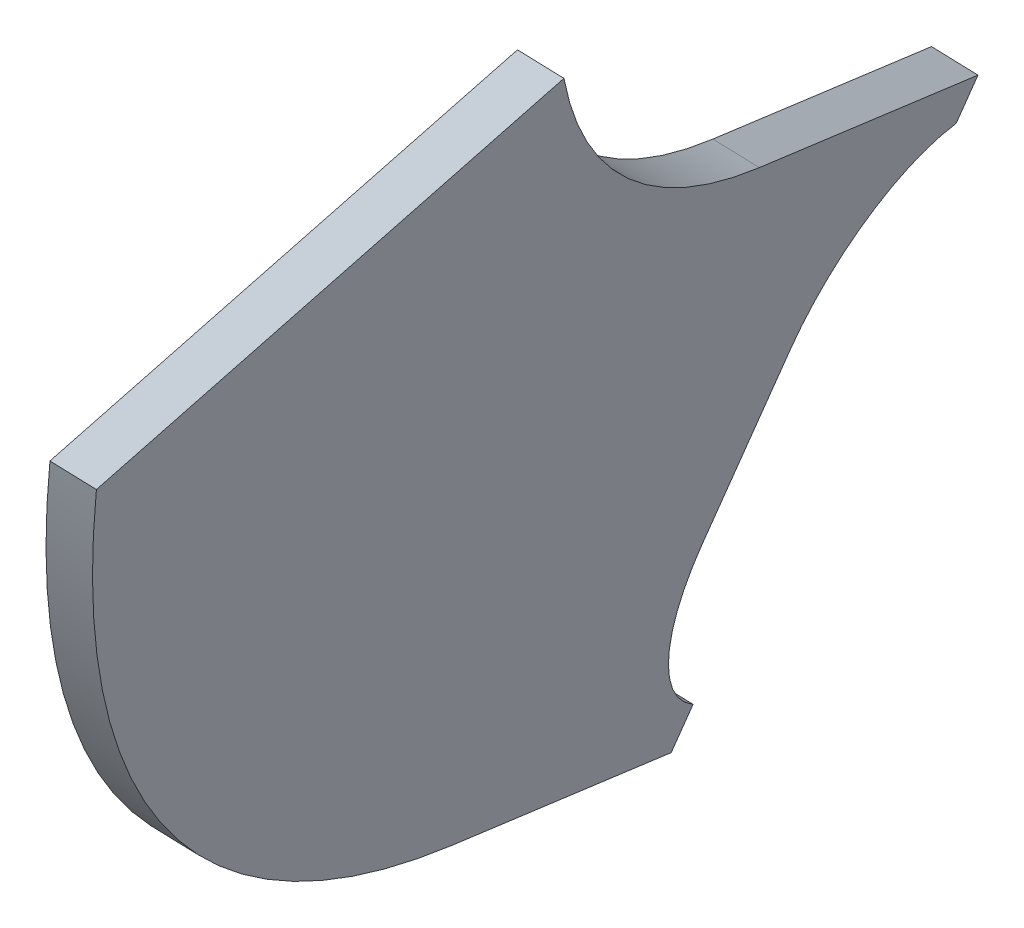
SolidWorks part; units mm, degrees
ref_plane "Front Plane" through (0, 0, 0) normal (0, 0, 1) x (1, 0, 0)
ref_plane "Top Plane" through (0, 0, 0) normal (0, 1, 0) x (1, 0, 0)
ref_plane "Right Plane" through (0, 0, 0) normal (1, 0, 0) x (0, 0, -1)
sketch "Sketch2" plane through (0, 0, 0) normal (0, 1, 0) x (1, 0, 0)
  line L0 (151.3, 0) -> (-151.3, 0) construction
  dimension "D1" = 302.6
ref_plane "Plane1" through (0, 0, 0) normal (0, 0.4067, 0.9135) x (-1, 0, 0)
sketch "Sketch3" plane through (0, 0, 0) normal (0, 0.4067, 0.9135) x (-1, 0, 0)
  line L0 (-136.8, 32.05) -> (-134.1, 32.05) construction
  line L1 (151.3, 176.2) -> (-151.3, 176.2) construction
  line L2 (151.3, 176.2) -> (151.3, 0) construction
  line L3 (151.3, 0) -> (-151.3, 0) construction
  line L4 (-151.3, 176.2) -> (-151.3, 0) construction
  line L5 (-151.3, 0) -> (151.3, 0) construction
  line L6 (-137.2598, 44.7696) -> (-140.8783, 19.0226) construction
  line L7 (-147.6, 46.65) -> (-134.1, 46.65) construction
  line L8 (-147.6, 46.65) -> (-147.6, 17.45) construction
  line L9 (-147.6, 17.45) -> (-134.1, 17.45) construction
  line L10 (-134.1, 46.65) -> (-134.1, 17.45) construction
  line L11 (-137.2598, 44.7696) -> (-142.6073, 45.5211) construction
  line L12 (-140.8783, 19.0226) -> (-146.2258, 19.7741) construction
  line L13 (-142.6073, 45.5211) -> (-146.2258, 19.7741) construction
  line L14 (-140.8783, 19.0226) -> (-133.9165, 18.0442) construction
  line L15 (-133.9165, 18.0442) -> (-134, 17.45) construction
  line L16 (-142.4371, 45.2952) -> (-137.4857, 44.5993)
  line L17 (-142.4371, 45.2952) -> (-145.9999, 19.9443)
  line L18 (-137.4857, 44.5993) -> (-141.0486, 19.2485)
  line L19 (-145.9999, 19.9443) -> (-141.0486, 19.2485)
  point P12 (-136.8, 32.05)
  dimension "D1" = 176.2
  dimension "D2" = 302.6
  dimension "D3" = 144.15
  dimension "D4" = 14.5
  dimension "D5" = 29.2
  dimension "D6" = 3.7
  dimension "D7" = 17.2
  dimension "D8" = 26
  dimension "D9" = 8
  dimension "D10" = 5.4
  dimension "D11" = 0.6
  dimension "D12" = 0.1
  dimension "D13" = 1.3742
  dimension "D14" = 5
  dimension "D15" = 0.2
  dimension "D16" = 0.2
  dimension "D17" = 0.2
extrude "Boss-Extrude1" add sketch "Sketch3" against normal blind 5
sketch "Sketch4" plane through (-3.4836, -22.6444, 10.0819) normal (-0.1392, -0.9047, 0.4028) x (0.9903, -0.1271, 0.0566)
  line L0 (152.7707, 16.0361) -> (147.2579, -3.1891) construction
  line L1 (142.3548, -5) -> (147.3548, 0) construction
  line L2 (152.7707, 16.0361) -> (151.2326, 16.4772) construction
  line L3 (151.2326, 16.4772) -> (146.3628, -0.506) construction
  line L4 (147.3548, -5) -> (147.3548, 0) construction
  line L5 (147.3548, -2.8514) -> (147.3548, -5)
  line L6 (147.3548, -5) -> (144.8548, -5)
  line L7 (142.3548, -5) -> (147.3548, -5) construction
  line L8 (147.2579, -3.1891) -> (147.3548, -2.8514)
  line L12 (142.3548, -2.5) -> (142.3548, -5)
  line L13 (142.3548, -5) -> (144.8548, -5)
  line L14 (142.3548, 0) -> (142.3548, -2.5)
  line L15 (142.3548, 0) -> (144.8548, 0)
  line L16 (144.8548, 0) -> (146.5079, 0)
  line L17 (146.5079, 0) -> (146.3628, -0.506)
  line L18 (142.3548, 0) -> (147.3548, 0) construction
  arc A0 (147.2579, -3.1891) -> (146.3628, -0.506) centre (144.8548, -2.5) cw construction
  arc A1 (144.8548, -5) -> (147.2579, -3.1891) centre (144.8548, -2.5) ccw
  arc A3 (142.3548, -2.5) -> (144.8548, -5) centre (144.8548, -2.5) ccw
  arc A4 (142.3548, -2.5) -> (144.8548, 0) centre (144.8548, -2.5) cw
  arc A5 (144.8548, 0) -> (146.3628, -0.506) centre (144.8548, -2.5) cw
  dimension "D2" = 2.5
  dimension "D1" = 1.6
  dimension "D3" = 16
  dimension "D4" = 20
extrude "Cut-Extrude1" cut sketch "Sketch4" against normal through all contours A1 L6 L8 | A3 L5 L6 | L5 A4 L8 | L8 A5 L17
ref_plane "Plane2" through (135.5824, -33.3758, -28.1152) normal (0.9519, -0.2343, -0.1974) x (-0.191, 0.0501, -0.9803)
sketch3d "3DSketch1"
  line L0 (149.6285, 0, 0) -> (156.8218, 0, 34.6885) construction
  line L1 (156.8218, 0, 34.6885) -> (151.3, -80.4834, 35.8335) construction
  line L2 (151.3, -160.9667, 71.667) -> (151.3, 0, 0) construction
  line L3 (151.3, 0, 0) -> (-151.3, 0, 0) construction
  line L4 (145.904, -19.5049, 5.1932) -> (150.827, -13.0853, 21.3129)
  line L5 (145.904, -19.5049, 5.1932) -> (142.3412, -42.664, 15.5044)
  line L6 (142.3412, -42.664, 15.5044) -> (147.2641, -36.2444, 31.624)
  line L7 (156.8218, 0, 34.6885) -> (162.2766, 0, 60.9937)
  line L8 (156.8218, 0, 34.6885) -> (160.157, 10.0034, 38.8972) construction
  line L9 (162.2766, 0, 60.9937) -> (160.157, 10.0034, 38.8972) construction
  line L10 (142.3412, -42.664, 15.5044) -> (139.9614, -42.0782, 15.9978) construction
  arc A0 (150.827, -13.0853, 21.3129) -> (156.8218, 0, 34.6885) centre (154.5149, 10.8871, 10.6397) ccw
  arc A1 (147.2641, -36.2444, 31.624) -> (162.2766, 0, 60.9937) centre (154.5149, 10.8871, 10.6397) ccw
  arc A2 (142.3412, -42.664, 15.5044) -> (141.4547, -41.4589, 17.9048) centre (139.9614, -42.0782, 15.9978) ccw construction
  point P5 (104.9215, 23.0954, 20.9237)
  point P10 (129.2903, 17.0966, 15.8704)
  point P20 (140.3093, -39.8166, 14.9909)
  dimension "D1" = 115
extrude "Boss-Extrude2" add sketch "3DSketch1" along direction (-0.9519, 0.2343, 0.1974) on the side of the normal blind 1.6 contours L7 A1 L6 L5 L4 A0
other "SurfaceCut1"
sketch "Sketch7" plane through (135.5824, -33.3758, -28.1152) normal (0.9519, -0.2343, -0.1974) x (-0.191, 0.0501, -0.9803)
  line L0 (-42.6605, 14.9503) -> (-33.5558, 10.8146)
  line L1 (-42.6605, 14.9503) -> (-49.443, 0.0185)
  line L2 (-33.5558, 10.8146) -> (-40.3382, -4.1171)
  line L3 (-49.443, 0.0185) -> (-40.3382, -4.1171)
  line L4 (-42.2406, -8.3053) -> (-31.6534, 15.0028) construction
  line L5 (-50.3507, 23.4957) -> (-33.9295, 16.0367) construction
  line L6 (-44.5168, -7.2714) -> (-60.9379, 0.1875) construction
  dimension "D1" = 4.6
  dimension "D2" = 4.6
  dimension "D3" = 10
extrude "Cut-Extrude2" cut sketch "Sketch7" against normal up to next
fillet "Fillet1" radius 5 2 edges at (146.5494, -20.8093, 13.9071) (144.267, -35.6456, 20.5127)
sketch "Sketch8" plane through (-3.4836, -22.6444, 10.0819) normal (-0.1392, -0.9047, 0.4028) x (-0.9903, 0.1271, -0.0566)
  circle A0 centre (-144.8548, 2.5) radius 0.9
  arc A1 (-146.3628, 0.506) -> (-147.2579, 3.1891) centre (-144.8548, 2.5) ccw construction
  dimension "D1" = 1.8
extrude "Cut-Extrude3" cut sketch "Sketch8" against normal through all
chamfer "Chamfer1" distance 1.1 angle 45 2 edges at (143.5242, -18.553, 6.5089) (139.9614, -42.4443, 15.1756)
ref_plane "Plane3" through (10.9248, 14.246, 35.772) normal (0.273, 0.3559, 0.8938) x (0.962, -0.101, -0.2536)
other "SurfaceCut2"
sketch "Sketch9" plane through (135.5824, -33.3758, -28.1152) normal (0.9519, -0.2343, -0.1974) x (-0.1917, 0.0472, -0.9803)
  line L46 (-60.2808, 1.4656) -> (-47.5756, -4.2601)
  line L47 (-47.5756, -4.2601) -> (-46.9195, -2.8043)
  line L48 (-48.8472, 5.0877) -> (-46.2177, 10.9226)
  line L49 (-39.0284, 14.706) -> (-38.3723, 16.1619)
  line L50 (-65.1392, 35.9356) -> (-88.9465, 37.0924)
  line L51 (-38.3723, 16.1619) -> (-51.0775, 21.8876)
  line L52 (-60.2808, 1.4656) -> (-47.5756, -4.2601)
  line L53 (-47.5756, -4.2601) -> (-46.9195, -2.8043)
  line L54 (-48.8472, 5.0877) -> (-46.2177, 10.9226)
  line L55 (-39.0284, 14.706) -> (-38.3723, 16.1619)
  line L56 (-65.1392, 35.9356) -> (-88.9465, 37.0924)
  line L57 (-38.3723, 16.1619) -> (-51.0775, 21.8876)
  line L58 (-38.1462, 12.7694) -> (-36.2562, 16.9632)
  line L59 (-36.2562, 16.9632) -> (-50.4202, 23.3463)
  line L60 (-64.0642, 37.4852) -> (-90.8974, 38.7891)
  line L61 (-60.9382, 0.0068) -> (-46.7743, -6.3762)
  line L62 (-46.7743, -6.3762) -> (-44.8843, -2.1824)
  line L63 (-47.3885, 4.4304) -> (-44.759, 10.2652)
  line L64 (-38.1462, 12.7694) -> (-36.2562, 16.9632)
  line L65 (-36.2562, 16.9632) -> (-50.4202, 23.3463)
  line L66 (-64.0642, 37.4852) -> (-90.8974, 38.7891)
  line L67 (-60.9382, 0.0068) -> (-46.7743, -6.3762)
  line L68 (-46.7743, -6.3762) -> (-44.8843, -2.1824)
  line L69 (-47.3885, 4.4304) -> (-44.759, 10.2652)
  arc A27 (-88.9465, 37.0924) -> (-60.2808, 1.4656) centre (-39.5327, 47.5053) ccw
  arc A28 (-48.8472, 5.0877) -> (-46.9195, -2.8043) centre (-42.83, 2.3761) ccw
  arc A29 (-39.0284, 14.706) -> (-46.2177, 10.9226) centre (-40.2005, 8.2109) ccw
  arc A30 (-65.1392, 35.9356) -> (-51.0775, 21.8876) centre (-39.5327, 47.5053) ccw
  arc A31 (-88.9465, 37.0924) -> (-60.2808, 1.4656) centre (-39.5327, 47.5053) ccw
  arc A32 (-48.8472, 5.0877) -> (-46.9195, -2.8043) centre (-42.83, 2.3761) ccw
  arc A33 (-39.0284, 14.706) -> (-46.2177, 10.9226) centre (-40.2005, 8.2109) ccw
  arc A34 (-65.1392, 35.9356) -> (-51.0775, 21.8876) centre (-39.5327, 47.5053) ccw
  arc A35 (-64.0642, 37.4852) -> (-50.4202, 23.3463) centre (-39.5327, 47.5053) ccw
  arc A36 (-90.8974, 38.7891) -> (-60.9382, 0.0068) centre (-39.5327, 47.5053) ccw
  arc A37 (-47.3885, 4.4304) -> (-44.8843, -2.1824) centre (-42.83, 2.3761) ccw
  arc A38 (-38.1462, 12.7694) -> (-44.759, 10.2652) centre (-40.2005, 8.2109) ccw
  arc A39 (-64.0642, 37.4852) -> (-50.4202, 23.3463) centre (-39.5327, 47.5053) ccw
  arc A40 (-90.8974, 38.7891) -> (-60.9382, 0.0068) centre (-39.5327, 47.5053) ccw
  arc A41 (-47.3885, 4.4304) -> (-44.8843, -2.1824) centre (-42.83, 2.3761) ccw
  arc A42 (-38.1462, 12.7694) -> (-44.759, 10.2652) centre (-40.2005, 8.2109) ccw
  dimension "D1" = 1.6
  dimension "D2" = 0
extrude "Cut-Extrude4" cut sketch "Sketch9" against normal up to next
equation "\"LCD_Height\"= 158mm"
equation "\"LCD_Width\"= 268mm"
equation "\"LCD_PCB_Height\"= 10mm"
equation "\"LCD_PCB_Width\"= 189"
equation "\"LCD_PCB_LOff\"= 38.5"
equation "\"LCD_Thick\"= 2.9mm"
equation "\"LCD_TBezel\"= 4.6mm"
equation "\"LCD_LBezel\"= 4.94mm"
equation "\"LCD_RBezel\"= 6.94mm"
equation "\"LCD_BBezel\"= 9.4mm"
equation "\"Wing_Height\"= 11.5mm"
equation "\"Wing_Width\"= 5mm"
equation "\"Wing_Corner\"= 1mm"
equation "\"Wing_Hole_VOff\"= 3.5mm"
equation "\"Wing_Hole_HOff\"= 2.8mm"
equation "\"Wing_Spacing\"= 128.9 + 2 * \"Wing_Hole_VOff\" - \"Wing_Height\""
equation "\"Wing_TOff\"= 8.35 - \"Wing_Hole_VOff\""
equation "\"Wing_DOff\"= 0.7mm"
equation "\"Wing_Thick\"= 0.3mm"
equation "\"Print_Gap\"= 0.2mm"
equation "\"Pin1_Pos\"= 89.75mm"
equation "\"Pin_Space\"= 0.5mm"
equation "\"Pin_num\"= 30"
equation "\"Min_Thick\"= 1.2mm"
equation "\"Nut_Width\"= 4.8mm"
equation "\"Nut_Height\"= 5.6mm"
equation "\"Nut_Thick\"= 1.6mm"
equation "\"Screw_Hole\"= 2.2mm"
equation "\"Screw_Chamf\"= 0.9mm"
equation "\"Bezel_Gap\"= 0.4mm"
equation "\"USB_Width\"= 16mm"
equation "\"Corner_Radius\"= 6mm"
equation "\"Stand_Tilt\"= 8"
equation "\"Screen_Tilt\"= 24"
equation "\"Stand_Splay\"= 16"
equation "\"D1@Sketch2\"=\"LCD_Width\" + \"Print_Gap\" + 2 * \"USB_Width\" + 2 * \"Min_Thick\""
equation "\"D1@Sketch3\"=\"Min_Thick\" + \"Print_Gap\" + \"LCD_Height\" + \"LCD_PCB_Height\" + \"Nut_Height\" + \"Min_Thick\""
equation "\"D2@Sketch3\"=\"LCD_Width\" + 2 * \"Min_Thick\" + 2 * \"USB_Width\" + \"Print_Gap\""
equation "\"D3@Sketch3\"=\"Min_Thick\" + \"Print_Gap\" / 2 + \"Nut_Height\" + \"Wing_TOff\" + \"Wing_Height\" - \"Wing_Hole_VOff\" + \"Wing_Spacing\""
equation "\"D4@Sketch3\"=\"Min_Thick\" + \"USB_Width\" + \"Print_Gap\" / 2 - \"Wing_Hole_HOff\""
equation "\"D5@Sketch3\"=\"Nut_Width\" + 2 * \"Min_Thick\" + 22"
equation "\"D6@Sketch3\"= 3 * \"Min_Thick\" + \"Print_Gap\" / 2"
equation "\"D9@Sketch3\"=\"Stand_Tilt\""
equation "\"D11@Sketch3\"=\"Min_Thick\" / 2"
equation "\"D12@Sketch3\"= \"Print_Gap\" / 2"
equation "\"D13@Sketch3\"=2.7 * tan(\"Stand_Splay\") + \"Min_Thick\" / 2"
equation "\"D15@Sketch3\"= \"Print_Gap\""
equation "\"D16@Sketch3\"= \"Print_Gap\""
equation "\"D17@Sketch3\"=\"Print_Gap\""
equation "\"D1@Sketch8\"=\"Screw_Hole\" - 2 *\"Print_Gap\" "
equation "\"D1@Chamfer1\"=\"Screw_Chamf\" + \"Print_Gap\""
equation "\"D3@Sketch4\"= \"Stand_Splay\""
